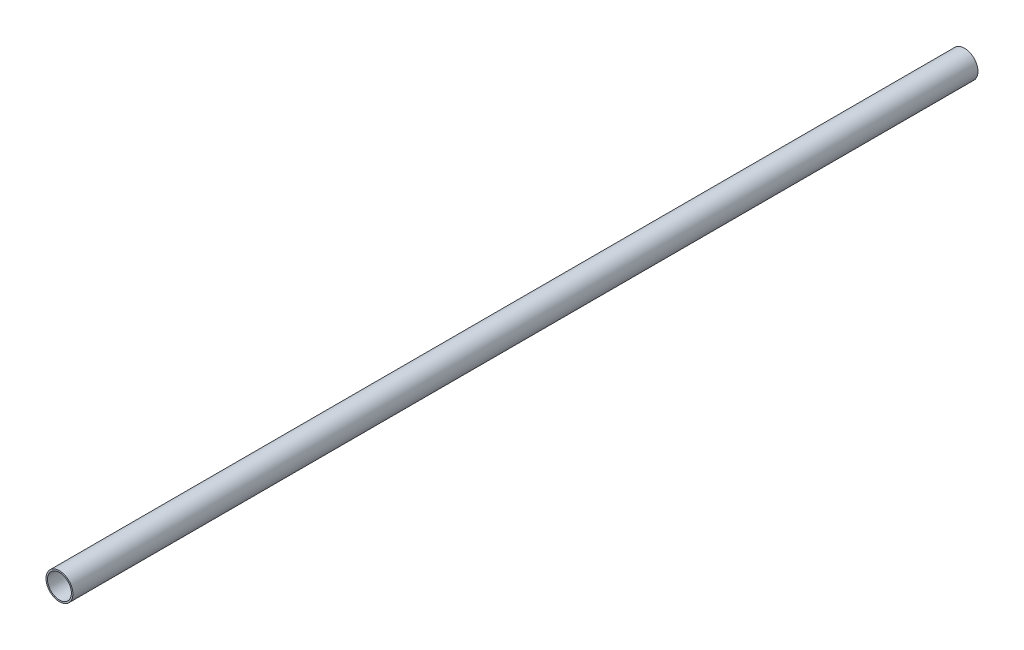
SolidWorks part; units mm, degrees
material "AISI 4130 Steel, annealed at 865C"
ref_plane "Front Plane" through (0, 0, 0) normal (0, 0, 1) x (1, 0, 0)
ref_plane "Top Plane" through (0, 0, 0) normal (0, 1, 0) x (1, 0, 0)
ref_plane "Right Plane" through (0, 0, 0) normal (1, 0, 0) x (0, 0, -1)
sketch "Sketch1" plane through (0, 0, 0) normal (0, 0, 1) x (1, 0, 0)
  circle A0 centre (0, 0) radius 7.9375
  circle A1 centre (0, 0) radius 7.0485
  dimension "D1" = 15.875
  dimension "D2" = 0.889
extrude "Boss-Extrude1" add sketch "Sketch1" along normal mid plane 533.4
